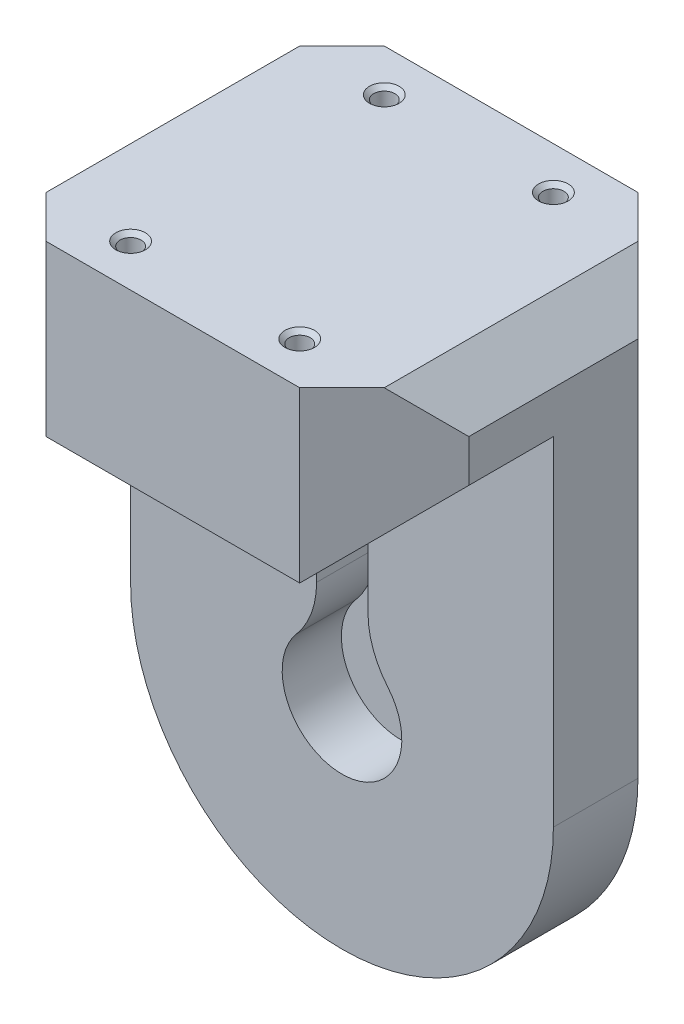
SolidWorks part; units mm, degrees
ref_plane "Front Plane" through (0, 0, 0) normal (0, 0, 1) x (1, 0, 0)
ref_plane "Top Plane" through (0, 0, 0) normal (0, 1, 0) x (1, 0, 0)
ref_plane "Right Plane" through (0, 0, 0) normal (1, 0, 0) x (0, 0, -1)
sketch "Sketch1" plane through (0, 0, 0) normal (0, 0, 1) x (1, 0, 0)
  line L0 (0, 0) -> (0, 147.804) construction
  line L4 (0, 150) -> (0, 0) construction
  line L6 (25, 50) -> (25, 0)
  line L7 (-25, 50) -> (-25, 0)
  line L8 (-25, 50) -> (25, 50)
  arc A2 (-25, 0) -> (25, 0) centre (0, 0) ccw
  point P5 (0, 0)
  point P7 (0, 75)
  dimension "D2" = 25
  dimension "D1" = 150
  dimension "D3" = 50
  dimension "D4" = 50
extrude "Boss-Extrude1" add sketch "Sketch1" along normal mid plane 20
chamfer "Chamfer1" distance 10 angle 45 3 edges at (-25, 25, -10) (0, -25, -10) (25, 25, -10)
sketch "Sketch6" plane through (0, 0, 10) normal (0, 0, 1) x (1, 0, 0)
  line L0 (0, 0) -> (0, 24.5) construction
  line L1 (3.075, 24.5) -> (3.075, 10.9818)
  line L2 (-3, 24.5) -> (-3, 11.0705)
  arc A0 (-5.3865, 4.587) -> (5.4176, 4.5503) centre (0, 0) ccw
  arc A1 (3.075, 24.5) -> (-3, 23.825) centre (0, 24.5) ccw
  arc A2 (-3, 11.0705) -> (-5.3865, 4.587) centre (-13, 11.0705) cw
  arc A3 (3.075, 10.9818) -> (5.4176, 4.5503) centre (13.075, 10.9818) ccw
  dimension "D1" = 14.15
  dimension "D3" = 6.15
  dimension "D4" = 10
  dimension "D2" = 24.5
extrude "Cut-Extrude3" cut sketch "Sketch6" against normal blind 7
sketch "Sketch7" plane through (0, 0, -10) normal (0, 0, -1) x (-1, 0, 0)
  circle A0 centre (0, 0) radius 4
  circle A1 centre (0, 24.5) radius 4
  dimension "D1" = 8
extrude "Cut-Extrude4" cut sketch "Sketch7" against normal blind 11
sketch "Sketch8" plane through (0, 0, 1) normal (0, 0, -1) x (-1, 0, 0)
  circle A0 centre (0, 24.5) radius 1.5
  circle A1 centre (0, 0) radius 1.5
  dimension "D1" = 3
extrude "Cut-Extrude5" cut sketch "Sketch8" against normal blind 11
sketch "Sketch9" plane through (0, 0, 10) normal (0, 0, 1) x (1, 0, 0)
  line L0 (-25, 50) -> (-25, 0) construction
  line L1 (25, 50) -> (-25, 50)
  line L2 (25, 50) -> (25, 30)
  line L3 (25, 30) -> (-25, 30)
  line L4 (-25, 50) -> (-25, 30)
  dimension "D1" = 20
extrude "Boss-Extrude2" add sketch "Sketch9" along normal blind 20
chamfer "Chamfer2" distance 10 angle 45 6 edges at (-25, 50, 15) (-25, 40, 30) (25, 50, 15) (25, 40, 30) (-25, 30, 20) (25, 30, 20)
chamfer "Chamfer3" distance 5 angle 45 2 edges at (-25, 50, 10) (25, 50, 10)
sketch "Sketch10" plane through (0, 50, 0) normal (0, 1, 0) x (1, 0, 0)
  line L0 (0, 10) -> (0, -30) construction
  line L1 (15, 10) -> (-15, 10) construction
  line L2 (15, -30) -> (-15, -30) construction
  line L3 (0, -10) -> (25, -10) construction
  line L4 (25, 0) -> (25, -20) construction
  circle A0 centre (10, 5) radius 1.25
  circle A1 centre (10, -25) radius 1.25
  circle A2 centre (-10, -25) radius 1.25
  circle A3 centre (-10, 5) radius 1.25
  dimension "D1" = 2.5
  dimension "D2" = 10
  dimension "D3" = 15
extrude "Cut-Extrude6" cut sketch "Sketch10" against normal blind 10
chamfer "Chamfer4" distance 0.5 angle 45 4 edges at (-10, 50, 26.25) (-10, 50, -6.25) (10, 50, 23.75) (10, 50, -3.75)
